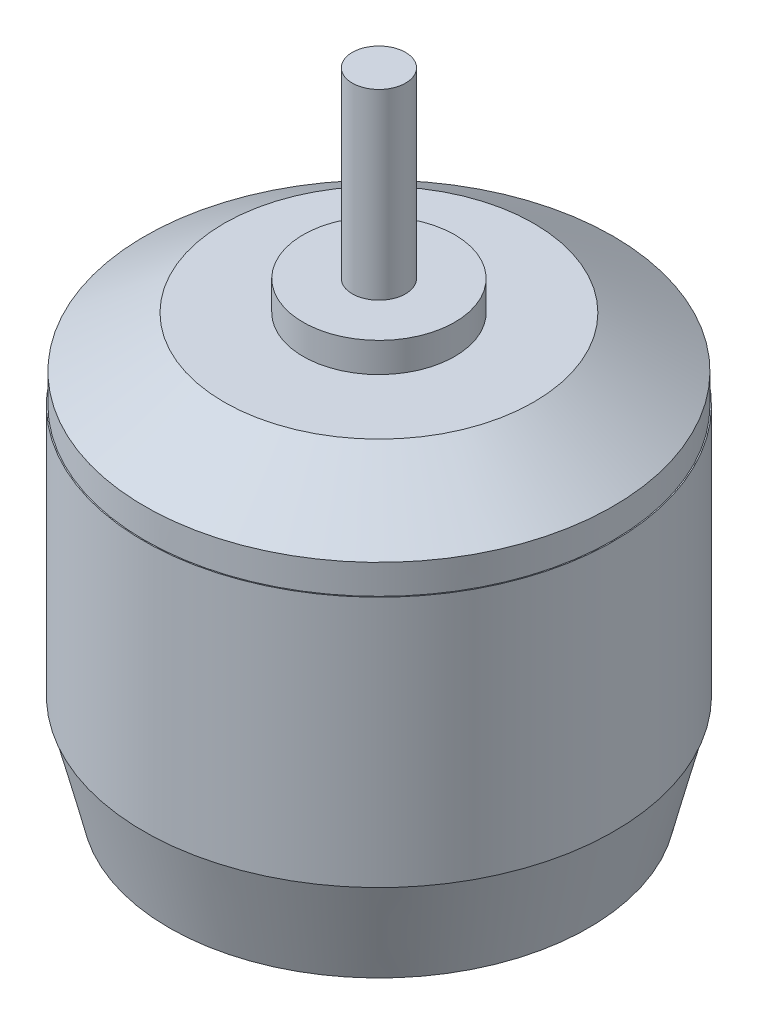
SolidWorks part; units mm, degrees
ref_plane "Front Plane" through (0, 0, 0) normal (0, 0, 1) x (1, 0, 0)
ref_plane "Top Plane" through (0, 0, 0) normal (0, 1, 0) x (1, 0, 0)
ref_plane "Right Plane" through (0, 0, 0) normal (1, 0, 0) x (0, 0, -1)
sketch "Sketch3" plane through (0, 0, 0) normal (0, 0, 1) x (1, 0, 0)
  line L0 (-13.8558, -5.713) -> (13.8442, -5.713) construction
  dimension "D1" = 27.7
sketch "Sketch4" plane through (0, 0, 0) normal (0, 0, 1) x (1, 0, 0)
  line L0 (0, 0) -> (1.5748, 0)
  line L1 (55, 0) -> (-55, 0) construction
  line L2 (1.5748, 0) -> (1.5748, 1.1049)
  line L3 (1.5748, 1.1049) -> (3.0099, 1.1049)
  line L4 (3.0099, 1.1049) -> (3.0099, 2.0574)
  line L5 (3.0099, 2.0574) -> (12.4079, 2.0574)
  line L6 (12.4079, 2.0574) -> (13.843, 7.747)
  line L8 (13.843, 7.747) -> (13.843, 24.3586)
  line L9 (13.843, 24.3586) -> (9.1567, 27.3558)
  line L10 (9.1567, 27.3558) -> (4.4831, 27.3558)
  line L11 (4.4831, 27.3558) -> (4.4831, 29.1084)
  line L12 (4.4831, 29.1084) -> (1.5748, 29.1084)
  line L13 (1.5748, 29.1084) -> (1.5748, 39.9034)
  line L14 (1.5748, 39.9034) -> (0, 39.9034)
  line L15 (0, -55) -> (0, 55) construction
  line L16 (0, 39.9034) -> (0, 0)
  point P11 (0, 0)
  point P15 (0, 0)
  point P21 (0, 0)
  dimension "D1" = 13.843
  dimension "D2" = 39.9034
  dimension "D3" = 1.7526
  dimension "D4" = 2.0574
  dimension "D5" = 1.5748
  dimension "D6" = 3.0099
  dimension "D7" = 1.1049
  dimension "D8" = 12.4079
  dimension "D9" = 5.6896
  dimension "D10" = 16.6116
  dimension "D11" = 10.795
  dimension "D12" = 9.1567
  dimension "D13" = 4.4831
ref_axis "Axis1" through (0, -72.3718, 0) along (0, 1, 0)
revolve "Revolve1" add sketch "Sketch4" angle 360 about axis through (0, -72.3718, 0) along (0, 1, 0)
sketch "Sketch5" plane through (0, 2.0574, 0) normal (0, -1, 0) x (1, 0, 0)
  line L0 (0, 0) -> (-50000, 0) construction
  line L1 (0, 0) -> (0, 50000) construction
  circle A0 centre (0, 0) radius 8
  circle A1 centre (0, 0) radius 9.5
  dimension "D1" = 19
  dimension "D2" = 16
hole_wizard "M3x0.5 Tapped Hole1" positions "Sketch6" profile "Sketch8" tap size "M3x0.5" standard "ANSI Metric"
sketch "Sketch6" plane through (0, 2.0574, 0) normal (0, -1, 0) x (-1, 0, 0)
  line L0 (-200000, 0) -> (250000, 0) construction
  circle A0 centre (0, 0) radius 8 construction
  point P0 (8, 0)
  point P6 (-8, 0)
sketch "Sketch8" plane through (-8, 2.0574, 0) normal (1, 0, 0) x (0, 0, -1)
  line L0 (0, 0) -> (0, 8.2511)
  line L1 (0, 8.2511) -> (1.25, 7.5)
  line L2 (1.25, 7.5) -> (1.25, 0.275)
  line L3 (1.25, 0.275) -> (1.525, 0)
  line L5 (1.525, 0) -> (0, 0)
  line L6 (-1.25, 0.275) -> (-1.525, 0) construction
  line L10 (0, 8.2511) -> (-1.25, 7.5) construction
  line L11 (0, -6.35) -> (0, 107.95) construction
  dimension "Tap Drill Dia." = 2.5
  dimension "Tap Drill Depth" = 7.5
  dimension "Near C'Sink Dia." = 3.05
  dimension "Near C'Sink Angle" = 90
  dimension "Drill Angle" = 118
cosmetic thread "Hole Thread1" parameters "D1"=6, "D2"=3
cosmetic thread "Hole Thread2" parameters "D1"=6, "D2"=3
hole_wizard "M3x0.5 Tapped Hole2" positions "Sketch9" profile "Sketch10" tap size "M3x0.5" standard "ANSI Metric"
sketch "Sketch9" plane through (0, 2.0574, 0) normal (0, -1, 0) x (-1, 0, 0)
  line L0 (0, 200000) -> (0, -250000) construction
  circle A0 centre (0, 0) radius 9.5 construction
  point P0 (0, 9.5)
  point P6 (0, -9.5)
sketch "Sketch10" plane through (0, 2.0574, -9.5) normal (1, 0, 0) x (0, 0, -1)
  line L0 (0, 0) -> (0, 8.2511)
  line L1 (0, 8.2511) -> (1.25, 7.5)
  line L2 (1.25, 7.5) -> (1.25, 0.275)
  line L3 (1.25, 0.275) -> (1.525, 0)
  line L5 (1.525, 0) -> (0, 0)
  line L6 (-1.25, 0.275) -> (-1.525, 0) construction
  line L10 (0, 8.2511) -> (-1.25, 7.5) construction
  line L11 (0, -6.35) -> (0, 107.95) construction
  dimension "Tap Drill Dia." = 2.5
  dimension "Tap Drill Depth" = 7.5
  dimension "Near C'Sink Dia." = 3.05
  dimension "Near C'Sink Angle" = 90
  dimension "Drill Angle" = 118
cosmetic thread "Hole Thread3" parameters "D1"=6, "D2"=3
cosmetic thread "Hole Thread4" parameters "D1"=6, "D2"=3
sketch "Sketch11" plane through (0, 0, 0) normal (0, 0, 1) x (1, 0, 0)
  line L0 (0, -72.3718) -> (0, 136.6368) construction
  line L1 (0, 22.6187) -> (13.9065, 22.6187)
  line L2 (0, 22.6187) -> (0, 7.747)
  line L3 (0, 7.747) -> (13.9065, 7.747)
  line L4 (13.9065, 22.6187) -> (13.9065, 7.747)
  line L8 (13.843, 7.747) -> (-13.843, 7.747) construction
  dimension "D1" = 13.9065
  dimension "D2" = 14.8717
revolve "Revolve2" add sketch "Sketch11" angle 360 about axis through (0, -72.3718, 0) along (0, 1, 0)
ref_plane "Can midplane" through (0, 15.1829, 0) normal (0, 1, 0) x (1, 0, 0)
